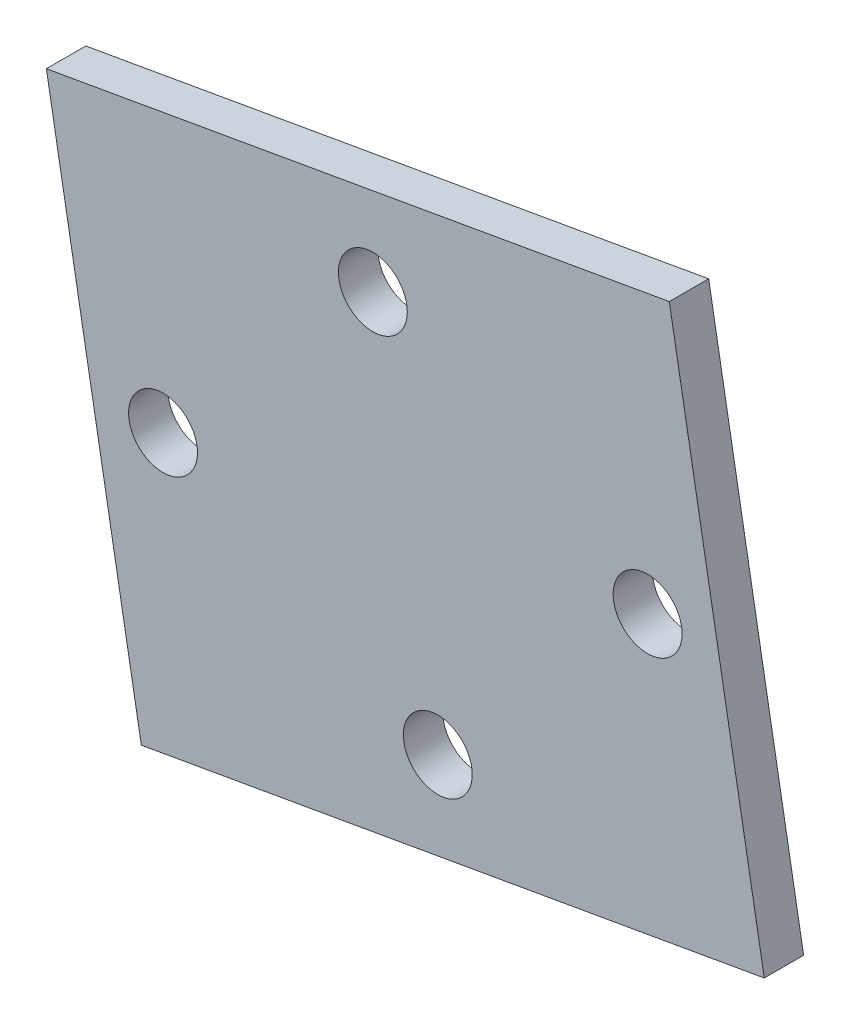
SolidWorks part; units mm, degrees
ref_plane "Front Plane" through (0, 0, 0) normal (0, 0, 1) x (1, 0, 0)
ref_plane "Top Plane" through (0, 0, 0) normal (0, 1, 0) x (1, 0, 0)
ref_plane "Right Plane" through (0, 0, 0) normal (1, 0, 0) x (0, 0, -1)
sketch "Sketch1" plane through (0, 0, 0) normal (0, 0, 1) x (-0.9848, -0.1736, 0)
  line L0 (-12.5, 0) -> (12.5, 0) construction
  line L1 (0, 9.5) -> (0, -9.5) construction
  line L3 (16.0682, -13.8863) -> (-16.0682, -13.8863)
  line L4 (16.0682, -13.8863) -> (16.0682, 13.8863)
  line L5 (16.0682, 13.8863) -> (-16.0682, 13.8863)
  line L6 (-16.0682, -13.8863) -> (-16.0682, 13.8863)
  line L7 (16.0682, -13.8863) -> (-16.0682, 13.8863) construction
  line L8 (16.0682, 13.8863) -> (-16.0682, -13.8863) construction
  circle A0 centre (0, 9.5) radius 1.75
  circle A1 centre (12.5, 0) radius 1.75
  circle A2 centre (0, -9.5) radius 1.75
  circle A3 centre (-12.5, 0) radius 1.75
  circle A4 centre (-12.5, 0) radius 3
  circle A5 centre (0, 9.5) radius 3
  circle A6 centre (12.5, 0) radius 3
  circle A7 centre (0, -9.5) radius 3
  point P0 (0, 0)
  point P15 (0, 0)
  dimension "D1" = 3.5
  dimension "D2" = 3.5
  dimension "D3" = 3.5
  dimension "D4" = 3.5
  dimension "D5" = 6
  dimension "D6" = 6
  dimension "D7" = 6
  dimension "D8" = 6
  dimension "D9" = 25
  dimension "D10" = 19
  dimension "D11" = 12.5
  dimension "D12" = 9.5
extrude "Boss-Extrude1" add sketch "Sketch1" along normal mid plane 2 contours L6 L3 L4 L5 A7 A6 A5 A4 | A4 A3 | A7 A2 | A5 A0 | A6 A1
